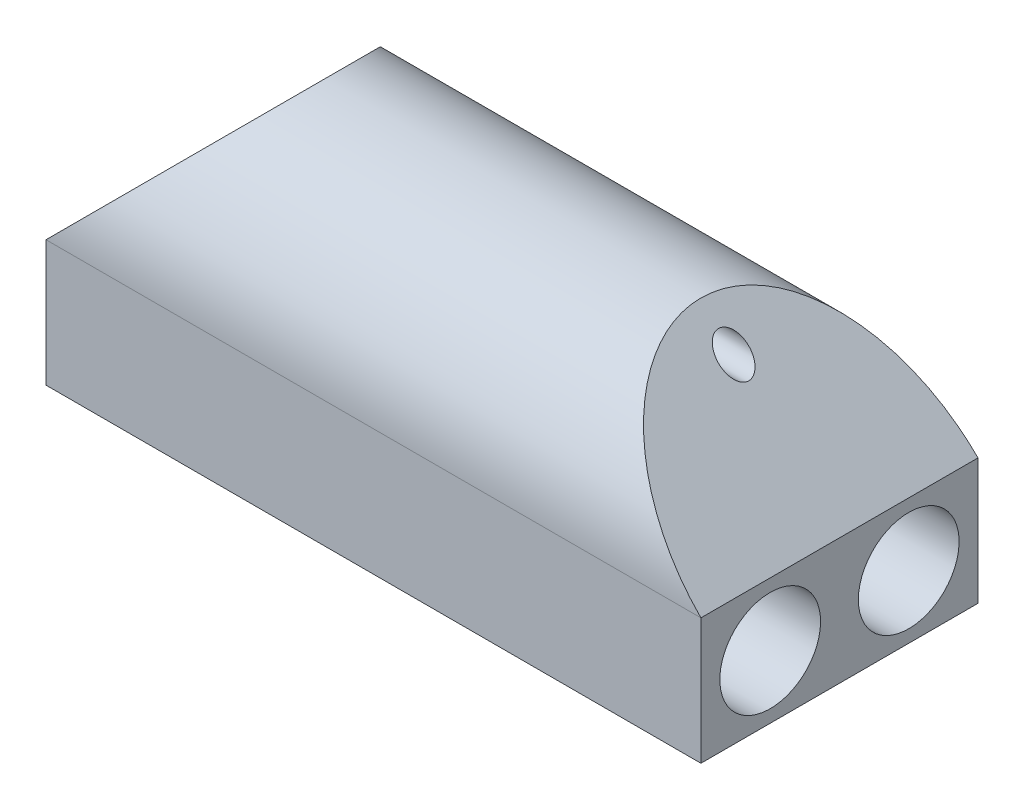
SolidWorks part; units mm, degrees
ref_plane "Front Plane" through (0, 0, 0) normal (0, 0, 1) x (1, 0, 0)
ref_plane "Top Plane" through (0, 0, 0) normal (0, 1, 0) x (1, 0, 0)
ref_plane "Right Plane" through (0, 0, 0) normal (1, 0, 0) x (0, 0, -1)
sketch "Sketch1" plane through (0, 0, 0) normal (0, 1, 0) x (1, 0, 0)
  line L1 (0, 0) -> (-33.02, 0)
  line L2 (0, 0) -> (0, 13.97)
  line L3 (0, 13.97) -> (-33.02, 13.97)
  line L4 (-33.02, 0) -> (-33.02, 13.97)
  dimension "length" = 33.02
  dimension "width" = 13.97
extrude "depth a" add sketch "Sketch1" along normal blind 6.35
sketch "Sketch4" plane through (0, 0, 0) normal (1, 0, 0) x (0, 0, -1)
  line L3 (0, 6.35) -> (13.97, 6.35) construction
  line L4 (0, 6.35) -> (13.97, 6.35)
  arc A0 (0, 6.35) -> (13.97, 6.35) centre (6.985, 6.35) cw
extrude "round extrude" add sketch "Sketch4" against normal up to surface (33.02 mm away) up to face at (-33.02, 3.175, -6.985)
sketch "Sketch5" plane through (0, 0, 0) normal (0, 0, 1) x (1, 0, 0)
  line L0 (0, 6.35) -> (0, 13.335)
  line L1 (0, 13.335) -> (-6.985, 13.335)
  line L2 (0, 13.335) -> (-33.02, 13.335) construction
  line L3 (-6.985, 13.335) -> (0, 6.35)
  line L4 (-16.51, -3.2288) -> (-16.51, 15.9288) construction
  line L6 (-33.02, 6.35) -> (-33.02, 13.335)
  line L7 (-33.02, 13.335) -> (-26.035, 13.335)
  line L8 (-26.035, 13.335) -> (-33.02, 6.35)
  line L9 (-33.02, 6.35) -> (0, 6.35) construction
  point P10 (-16.51, 6.35)
  point P13 (0, 0)
  point P16 (-16.51, 6.35)
  dimension "D1" = 45
extrude "angle cut" cut sketch "Sketch5" against normal through all
sketch "string hole " plane through (0, 0, 0) normal (1, 0, 0) x (0, 0, -1)
  line L0 (6.985, 6.35) -> (6.985, 13.335) construction
  line L1 (13.97, 6.35) -> (0, 6.35) construction
  circle A0 centre (6.985, 11.684) radius 0.762
  arc A1 (13.97, 6.35) -> (0, 6.35) centre (6.985, 6.35) ccw construction
  point P9 (0, 0)
  dimension "D1" = 1.524
  dimension "D2" = 5.334
extrude "string hole cut" cut sketch "string hole " against normal through all
sketch "elastic holes" plane through (0, 0, 0) normal (1, 0, 0) x (0, 0, -1)
  line L1 (13.97, 6.35) -> (0, 6.35) construction
  line L2 (0, 0) -> (13.97, 0) construction
  line L3 (6.985, 0) -> (6.985, 6.35) construction
  line L5 (6.985, 3.175) -> (0, 3.175) construction
  line L7 (0, 6.35) -> (0, 0) construction
  circle A0 centre (3.4925, 3.175) radius 2.54
  circle A1 centre (10.4775, 3.175) radius 2.54
  point P1 (0, 0)
  point P5 (6.985, 6.35)
  point P8 (3.4925, 3.175)
  point P11 (0, 0)
  point P13 (6.985, 3.175)
  point P17 (6.985, 0)
  point P20 (0, 3.175)
  dimension "D1" = 5.08
extrude "elastic hole cut" cut sketch "elastic holes" against normal through all
